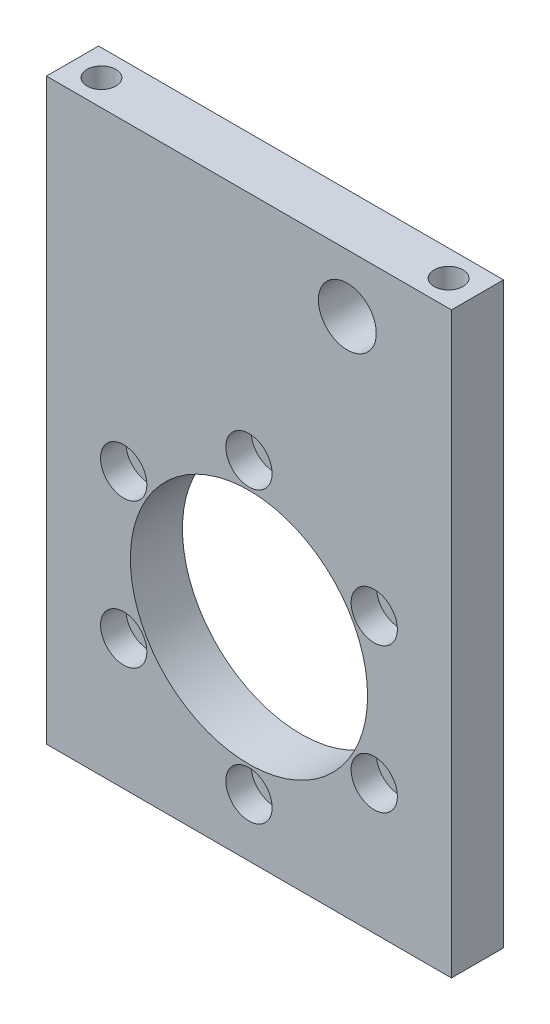
SolidWorks part; units mm, degrees
material "1060 Alloy"
ref_plane "Front Plane" through (0, 0, 0) normal (0, 0, 1) x (1, 0, 0)
ref_plane "Top Plane" through (0, 0, 0) normal (0, 1, 0) x (1, 0, 0)
ref_plane "Right Plane" through (0, 0, 0) normal (1, 0, 0) x (0, 0, -1)
sketch "Sketch1" plane through (0, 0, 0) normal (0, 0, 1) x (1, 0, 0)
  line L1 (0, 0) -> (70, 0)
  line L2 (0, 0) -> (0, 100)
  line L3 (0, 100) -> (70, 100)
  line L4 (70, 0) -> (70, 100)
  dimension "D1" = 70
  dimension "D2" = 100
extrude "Boss-Extrude1" add sketch "Sketch1" along normal mid plane 9
sketch "Sketch3" plane through (0, 0, 0) normal (0, 0, 1) x (1, 0, 0)
  circle A0 centre (35, 35) radius 20.5
  dimension "D1" = 41
  dimension "D2" = 35
  dimension "D3" = 35
extrude "Cut-Extrude2" cut sketch "Sketch3" against normal through all both and the other way through all
hole_wizard "M6 Tapped Hole1" positions "Sketch4" profile "Sketch5" tap size "M6" standard "ISO"
sketch "Sketch4" plane through (0, 0, 0) normal (0, -1, 0) x (-1, 0, 0)
  line L0 (-70, -4.5) -> (-70, 4.5) construction
  line L1 (0, -4.5) -> (0, 4.5) construction
  point P0 (-65, 0)
  point P2 (-5, 0)
  dimension "D1" = 5
  dimension "D2" = 5
sketch "Sketch5" plane through (65, 0, 0) normal (1, 0, 0) x (0, 0, -1)
  line L0 (0, 0) -> (0, 16.5022)
  line L1 (0, 16.5022) -> (2.5, 15)
  line L2 (2.5, 15) -> (2.5, 0)
  line L5 (2.5, 0) -> (0, 0)
  line L10 (0, 16.5022) -> (-2.5, 15) construction
  line L11 (0, -6.35) -> (0, 107.95) construction
  dimension "Tap Drill Dia." = 5
  dimension "Tap Drill Depth" = 15
  dimension "Drill Angle" = 118
cosmetic thread "Hole Thread1" parameters "D1"=12, "D2"=6
cosmetic thread "Hole Thread2" parameters "D1"=12, "D2"=6
ref_plane "Plane1" through (0, 50, 0) normal (0, 1, 0) x (1, 0, 0)
mirror "Mirror1" about plane through (0, 50, 0) normal (0, 1, 0) of "M6 Tapped Hole1"
hole_wizard "CBORE for M4 Hex Socket Head Cap Screw1" positions "Sketch6" profile "Sketch7" counterbore size "M4" standard "ISO" end condition through all
sketch "Sketch6" plane through (0, 0, 4.5) normal (0, 0, 1) x (1, 0, 0)
  line L0 (14.5, 35) -> (55.5, 35) construction
  circle A0 centre (35, 35) radius 20.5 construction
  point P0 (35, 60)
  point P16 (35, 35)
  dimension "D1" = 25
sketch "Sketch7" plane through (35, 60, 4.5) normal (1, 0, 0) x (0, -1, 0)
  line L0 (0, 0) -> (0, 9)
  line L1 (0, 9) -> (2.15, 9)
  line L3 (2.15, 9) -> (2.15, 4.4)
  line L4 (2.15, 4.4) -> (4, 4.4)
  line L5 (4, 4.4) -> (4, 0)
  line L7 (4, 0) -> (0, 0)
  line L11 (0, -6.35) -> (0, 107.95) construction
  dimension "Thru Hole Dia." = 4.3
  dimension "Thru Hole Depth" = 9
  dimension "C'Bore Dia." = 8
  dimension "C'Bore Depth" = 4.4
pattern_circular "CirPattern1" count 6 over 360 about axis through (35, 35, 0) along (0, 0, 1) of "CBORE for M4 Hex Socket Head Cap Screw1"
sketch "Sketch8" plane through (0, 0, 4.5) normal (0, 0, 1) x (1, 0, 0)
  line L0 (70, 100) -> (0, 100) construction
  line L1 (70, 0) -> (70, 100) construction
  circle A0 centre (52, 90) radius 5
  dimension "D1" = 10
  dimension "D2" = 10
  dimension "D3" = 18
extrude "Cut-Extrude3" cut sketch "Sketch8" against normal blind 10
move or copy body "Body-Move/Copy1" [suppressed] bodies to move or copy 113
